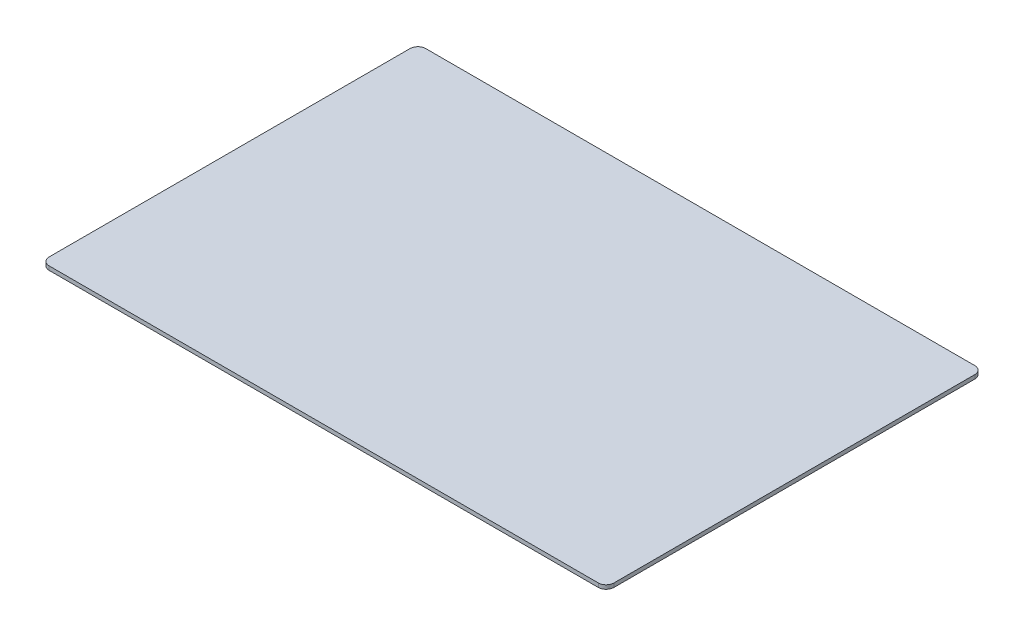
SolidWorks part; units mm, degrees
material "PC High Viscosity"
ref_plane "Front Plane" through (0, 0, 0) normal (0, 0, 1) x (1, 0, 0)
ref_plane "Top Plane" through (0, 0, 0) normal (0, 1, 0) x (1, 0, 0)
ref_plane "Right Plane" through (0, 0, 0) normal (1, 0, 0) x (0, 0, -1)
sketch "Sketch1" plane through (0, 0, 0) normal (0, 1, 0) x (1, 0, 0)
  line L1 (-228.6, -152.4) -> (228.6, -152.4)
  line L2 (-228.6, -152.4) -> (-228.6, 152.4)
  line L3 (-228.6, 152.4) -> (228.6, 152.4)
  line L4 (228.6, -152.4) -> (228.6, 152.4)
  line L5 (-228.6, -152.4) -> (228.6, 152.4) construction
  line L6 (-228.6, 152.4) -> (228.6, -152.4) construction
  point P0 (0, 0)
  dimension "D1" = 457.2
  dimension "D2" = 304.8
extrude "Boss-Extrude1" add sketch "Sketch1" along normal blind 3.175
fillet "Fillet1" radius 6.35 4 edges at (-228.6, 1.5875, -152.4) (228.6, 1.5875, -152.4) (228.6, 1.5875, 152.4) (-228.6, 1.5875, 152.4)
